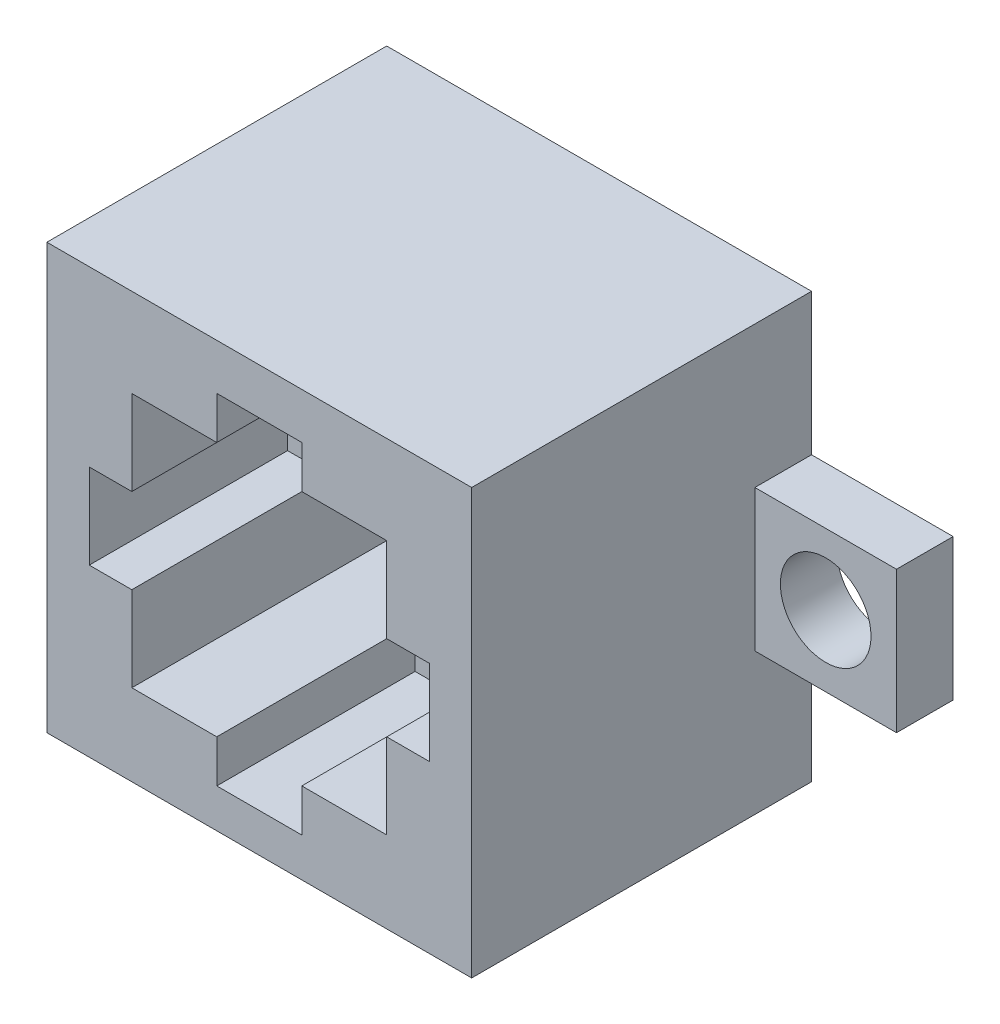
SolidWorks part; units mm, degrees
ref_plane "Front Plane" through (0, 0, 0) normal (0, 0, 1) x (1, 0, 0)
ref_plane "Top Plane" through (0, 0, 0) normal (0, 1, 0) x (1, 0, 0)
ref_plane "Right Plane" through (0, 0, 0) normal (1, 0, 0) x (0, 0, -1)
ref_plane "Plane4" through (0, 0, 0) normal (0, 0, -1) x (-1, 0, 0)
sketch "Sketch1" plane through (0, 0, 0) normal (0, 0, -1) x (-1, 0, 0)
  line L0 (55, 69) -> (55, 84)
  line L1 (55, 84) -> (40, 84)
  line L2 (40, 84) -> (40, 69)
  line L3 (40, 69) -> (55, 69)
extrude "Boss-Extrude1" add sketch "Sketch1" against normal blind 12
sketch "Sketch2" plane through (0, 0, 12) normal (0, 0, 1) x (1, 0, 0)
  line L0 (-43, 71.875) -> (-43, 80.875)
  line L1 (-43, 80.875) -> (-52, 80.875)
  line L2 (-52, 80.875) -> (-52, 71.875)
  line L3 (-52, 71.875) -> (-43, 71.875)
extrude "Cut-Extrude1" cut sketch "Sketch2" against normal blind 11.002
sketch "Sketch3" plane through (0, 0, 0) normal (0, 0, -1) x (-1, 0, 0)
  line L0 (50.753, 73.123) -> (50.753, 79.628)
  line L1 (50.753, 79.628) -> (44.248, 79.628)
  line L2 (44.248, 79.628) -> (44.248, 73.123)
  line L3 (44.248, 73.123) -> (50.753, 73.123)
extrude "Cut-Extrude2" cut sketch "Sketch3" against normal through all
sketch "Sketch4" plane through (0, 71.875, 0) normal (0, 1, 0) x (-1, 0, 0)
  line L0 (45.999, 12) -> (45.999, 4.998)
  line L1 (45.999, 4.998) -> (49.001, 4.998)
  line L2 (49.001, 4.998) -> (49.001, 12)
  line L3 (49.001, 12) -> (45.999, 12)
extrude "Cut-Extrude3" cut sketch "Sketch4" against normal blind 1.502
sketch "Sketch5" plane through (-43, 0, 0) normal (-1, 0, 0) x (0, 0, 1)
  line L0 (12, 77.876) -> (4.998, 77.876)
  line L1 (4.998, 77.876) -> (4.998, 74.874)
  line L2 (4.998, 74.874) -> (12, 74.874)
  line L3 (12, 74.874) -> (12, 77.876)
extrude "Cut-Extrude4" cut sketch "Sketch5" against normal blind 1.502
sketch "Sketch6" plane through (-52, 0, 0) normal (1, 0, 0) x (0, 0, -1)
  line L0 (-12, 74.874) -> (-4.998, 74.874)
  line L1 (-4.998, 74.874) -> (-4.998, 77.876)
  line L2 (-4.998, 77.876) -> (-12, 77.876)
  line L3 (-12, 77.876) -> (-12, 74.874)
extrude "Cut-Extrude5" cut sketch "Sketch6" against normal blind 1.503
sketch "Sketch7" plane through (0, 80.875, 0) normal (0, -1, 0) x (1, 0, 0)
  line L0 (-49.001, 12) -> (-49.001, 4.998)
  line L1 (-49.001, 4.998) -> (-45.999, 4.998)
  line L2 (-45.999, 4.998) -> (-45.999, 12)
  line L3 (-45.999, 12) -> (-49.001, 12)
extrude "Cut-Extrude6" cut sketch "Sketch7" against normal blind 1.503
sketch "Sketch9" plane through (-55, 0, 0) normal (-1, 0, 0) x (0, 0, 1)
  line L0 (0, 69) -> (0, 84) construction
  line L1 (0, 79) -> (2, 79)
  line L2 (0, 79) -> (0, 74)
  line L3 (0, 74) -> (2, 74)
  line L4 (2, 79) -> (2, 74)
  line L5 (12, 84) -> (0, 84) construction
  line L6 (12, 69) -> (0, 69) construction
  dimension "D1" = 5
  dimension "D2" = 5
  dimension "D3" = 2
extrude "Boss-Extrude2" add sketch "Sketch9" along normal blind 5
sketch "Sketch10" plane through (-40, 0, 0) normal (1, 0, 0) x (0, 0, -1)
  line L0 (0, 84) -> (0, 69) construction
  line L1 (0, 79) -> (-2, 79)
  line L2 (0, 79) -> (0, 74)
  line L3 (0, 74) -> (-2, 74)
  line L4 (-2, 79) -> (-2, 74)
  line L5 (-12, 84) -> (0, 84) construction
  line L6 (-12, 69) -> (0, 69) construction
  dimension "D1" = 5
  dimension "D2" = 5
  dimension "D3" = 2
extrude "Boss-Extrude3" add sketch "Sketch10" along normal blind 5
sketch "Sketch11" plane through (0, 0, 2) normal (0, 0, 1) x (1, 0, 0)
  line L0 (-37.5, 79) -> (-37.5, 74) construction
  line L1 (-35, 79) -> (-40, 79) construction
  line L2 (-35, 74) -> (-40, 74) construction
  line L3 (-57.5, 79) -> (-57.5, 74) construction
  line L4 (-60, 79) -> (-55, 79) construction
  line L5 (-60, 74) -> (-55, 74) construction
  circle A0 centre (-37.5, 76.5) radius 1.6
  circle A1 centre (-57.5, 76.5) radius 1.6
extrude "Cut-Extrude7" cut sketch "Sketch11" against normal blind 5
